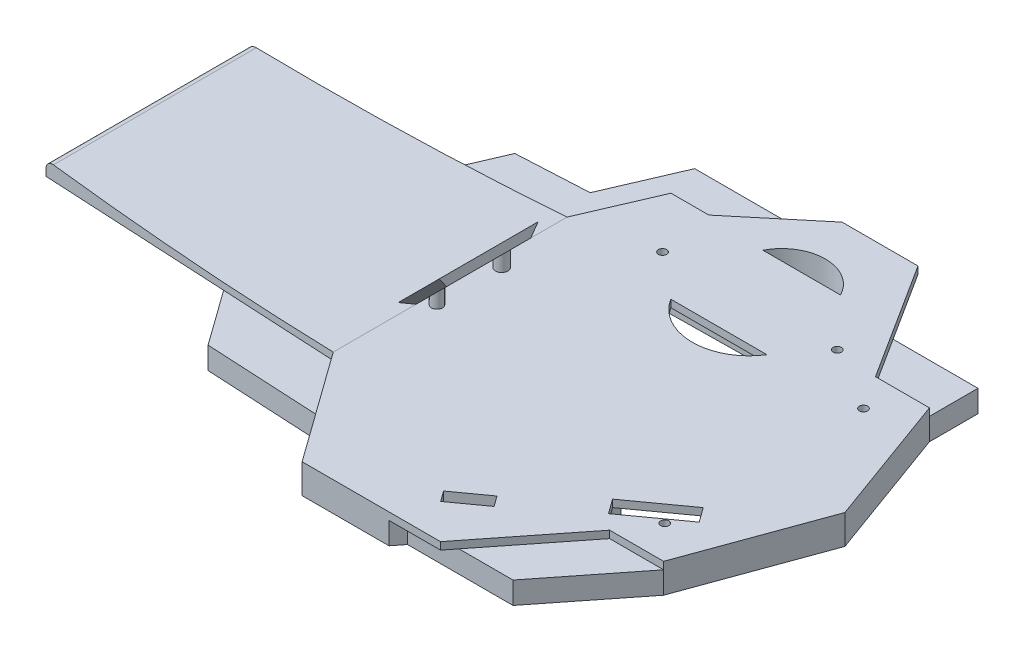
SolidWorks part; units mm, degrees
ref_plane "前视基准面" through (0, 0, 0) normal (0, 0, 1) x (1, 0, 0)
ref_plane "上视基准面" through (0, 0, 0) normal (0, 1, 0) x (1, 0, 0)
ref_plane "右视基准面" through (0, 0, 0) normal (1, 0, 0) x (0, 0, -1)
other "Configuration Table"
sketch "草图2" plane through (0, 0, 0) normal (0, 1, 0) x (1, 0, 0)
  line L0 (0, 0) -> (243.6421, 0) construction
  line L30 (176.8295, 36.1855) -> (82.5273, -31.8251) construction
  line L35 (141.8216, 68.0827) -> (121.1619, 68.0827)
  line L36 (176.8295, 36.1855) -> (190, 0)
  line L37 (104.1466, -61.9173) -> (82.5273, -31.8251)
  line L38 (82.5273, -31.8251) -> (0, -27.5)
  line L39 (0, -27.5) -> (0, 27.5)
  line L40 (0, 27.5) -> (82.5273, 31.8251)
  line L43 (190, 0) -> (176.8295, -36.1855)
  line L45 (82.5273, 31.8251) -> (91.0398, 51.6089)
  line L51 (104.1466, -61.9173) -> (190, 0) construction
  line L53 (141.8216, -61.9173) -> (104.1466, -61.9173)
  line L55 (82.5273, 31.8251) -> (342.4089, 31.8251) construction
  line L57 (176.8295, 36.1855) -> (176.8295, 0) construction
  line L58 (176.8295, 0) -> (176.8295, -36.1855) construction
  line L59 (82.5273, -31.8251) -> (342.4089, -31.8251) construction
  line L62 (91.0398, 51.6089) -> (101.351, 51.6089)
  line L63 (101.351, 51.6089) -> (121.1619, 68.0827)
  line L64 (141.8216, 68.0827) -> (162.1337, 36.1855)
  line L65 (162.1337, 36.1855) -> (176.8295, 36.1855)
  line L66 (176.8295, -36.1855) -> (162.1337, -36.1855)
  line L67 (162.1337, -36.1855) -> (141.8216, -61.9173)
  dimension "D1" = 190
  dimension "D2" = 130
  dimension "D4" = 55
  dimension "D6" = 93
  dimension "D7" = 93
  dimension "D8" = 140
extrude "凸台-拉伸1" add sketch "草图2" along normal blind 2
sketch "草图6" plane through (0, 2, 0) normal (0, 1, 0) x (1, 0, 0)
  line L0 (82.5273, 31.8251) -> (82.5273, -31.8251)
  line L1 (82.5273, -31.8251) -> (0, -27.5)
  line L2 (0, -27.5) -> (0, 27.5)
  line L3 (0, 27.5) -> (82.5273, 31.8251)
extrude "凸台-拉伸2" add sketch "草图6" along normal blind 2
sketch "草图7" plane through (0, 0, 0) normal (0, 0, 1) x (1, 0, 0)
  line L2 (82.5273, 2) -> (82.5273, 30.7408)
  line L3 (82.5273, 30.7408) -> (0, 4)
  spline S0 degree 2 poles (82.5273, 2) (41.2153, 1.0012) (0, 4) knots 0 0 0 1 1 1
extrude "切除-拉伸3" cut sketch "草图7" against normal through all both and the other way through all
fillet "圆角1" radius 2 1 edges at (0, 4, 0)
ref_plane "基准面3" through (0, -12, 0) normal (0, -1, 0) x (-1, 0, 0)
sketch "草图10" plane through (0, 0, 0) normal (0, -1, 0) x (1, 0, 0)
  line L0 (0, 27.5) -> (82.5273, 31.8251)
  line L1 (82.5273, 31.8251) -> (171.8529, 31.8251)
  line L2 (171.8529, 31.8251) -> (171.8529, -31.8251)
  line L3 (171.8529, -31.8251) -> (82.5273, -31.8251)
  line L4 (82.5273, -31.8251) -> (0, -27.5)
  line L5 (0, -27.5) -> (0, 27.5)
sketch "草图12" plane through (0, 2, 0) normal (0, 1, 0) x (1, 0, 0)
  line L0 (176.8295, 36.1855) -> (82.5273, -31.8251)
  line L1 (190, 0) -> (104.1466, -61.9173)
  line L2 (183.4148, 18.0928) -> (93.337, -46.8712) construction
  line L3 (190, 0) -> (176.8295, 36.1855) construction
  line L4 (82.5273, -31.8251) -> (104.1466, -61.9173) construction
sketch "草图13" plane through (0, 0, 0) normal (0, -1, 0) x (1, 0, 0)
  line L0 (53.5015, -30.3039) -> (58.4123, -41.717)
  line L1 (82.5273, -31.8251) -> (0, -27.5) construction
  line L2 (58.4123, -41.717) -> (77.9269, -42.7397)
  line L3 (77.9269, -42.7397) -> (86.4844, -62.6282)
  line L4 (86.4844, -62.6282) -> (136.1647, -62.6282)
  line L5 (176.8295, 36.1855) -> (190, 0)
  line L6 (190, 0) -> (176.8295, -36.1855)
  line L7 (136.1647, -62.6282) -> (144.5841, -49.4069)
  line L8 (144.5841, -49.4069) -> (176.8295, -49.4069)
  line L9 (176.8295, -49.4069) -> (176.8295, -36.1855)
  line L11 (176.8295, 36.1855) -> (158.7432, 59.0976)
  line L12 (158.7432, 59.0976) -> (130.0164, 59.0976)
  line L13 (130.0164, 59.0976) -> (127.7906, 61.9173)
  line L14 (104.1466, 61.9173) -> (141.8216, 61.9173) construction
  line L15 (127.7906, 61.9173) -> (104.1466, 61.9173)
  line L16 (104.1466, 61.9173) -> (93.337, 46.8712)
  line L17 (93.337, 46.8712) -> (61.8459, 45.2208)
  line L18 (61.8459, 45.2208) -> (51.0363, 30.1747)
  line L19 (0, 27.5) -> (82.5273, 31.8251) construction
  line L20 (51.0363, 30.1747) -> (171.8529, 31.8251)
  line L21 (171.8529, 31.8251) -> (171.8529, -31.8251)
  line L22 (171.8529, -31.8251) -> (53.5015, -30.3039)
extrude "凸台-拉伸4" add sketch "草图13" along normal blind 6 contours L18 L20 L21 L22 L0 L2 L3 L4 L7 L8 L9 L6 L5 L11 L12 L13 L15 L16 L17
sketch "草图17" plane through (0, 2, 0) normal (0, 1, 0) x (1, 0, 0)
  line L3 (116.0112, 26.5953) -> (142.1812, 26.5953)
  line L4 (138.1274, 50.6813) -> (116.9896, 50.6813)
  arc A1 (116.0112, 26.5953) -> (142.1812, 26.5953) centre (129.0962, 34.7996) ccw
  arc A2 (116.9896, 50.6813) -> (138.1274, 50.6813) centre (127.5585, 45.2443) cw
sketch "草图18" plane through (0, 2, 0) normal (0, 1, 0) x (1, 0, 0)
  line L4 (169.5639, -18.1259) -> (155.2183, -28.4719)
  line L5 (172.4314, -22.1019) -> (169.5639, -18.1259)
  line L6 (158.0858, -32.4479) -> (172.4314, -22.1019)
  line L7 (155.2183, -28.4719) -> (158.0858, -32.4479)
  line L8 (169.5639, -18.1259) -> (155.2183, -28.4719)
  line L9 (172.4314, -22.1019) -> (169.5639, -18.1259)
  line L10 (158.0858, -32.4479) -> (172.4314, -22.1019)
  line L11 (155.2183, -28.4719) -> (158.0858, -32.4479)
  line L12 (130.3021, -49.5646) -> (132.3616, -52.4203)
  line L13 (132.3616, -52.4203) -> (140.8147, -46.3239)
  line L14 (140.8147, -46.3239) -> (138.7552, -43.4683)
  line L15 (138.7552, -43.4683) -> (130.3021, -49.5646)
  line L16 (130.3021, -49.5646) -> (132.3616, -52.4203)
  line L17 (132.3616, -52.4203) -> (140.8147, -46.3239)
  line L18 (140.8147, -46.3239) -> (138.7552, -43.4683)
  line L19 (138.7552, -43.4683) -> (130.3021, -49.5646)
  dimension "D1" = 0
  dimension "D2" = 0
extrude "切除-拉伸7" cut sketch "草图18" against normal through all
sketch "草图19" plane through (0, 2, 0) normal (0, 1, 0) x (1, 0, 0)
  line L0 (82.5273, -31.8251) -> (176.8295, 36.1855)
  line L1 (176.8295, 36.1855) -> (190, 0)
  line L2 (190, 0) -> (104.1466, -61.9173)
  line L3 (104.1466, -61.9173) -> (82.5273, -31.8251)
ref_plane "基准面4" through (40.2637, -40.2637, 0) normal (-0.7071, 0.7071, 0) x (0, 0, -1)
sketch "草图23" plane through (40.2637, -40.2637, 0) normal (-0.7071, 0.7071, 0) x (0, 0, -1)
  line L0 (-9.292, -59.7699) -> (13.6381, -59.7699)
  line L1 (-31.8251, -59.7699) -> (31.8251, -59.7699) construction
  line L2 (13.6381, -59.7699) -> (13.6381, -71.5206)
  line L3 (13.6381, -71.5206) -> (-9.292, -71.5206)
  line L4 (-9.292, -71.5206) -> (-9.292, -60.8098)
  line L5 (-9.292, -60.8098) -> (-9.292, -59.7699)
  point P7 (0, 0)
extrude "凸台-拉伸5" add sketch "草图23" along normal blind 2 draft 45 separate body draft outward yes
sketch "草图24" plane through (0, 2, 0) normal (0, 1, 0) x (1, 0, 0)
  circle A0 centre (85.4903, 11.0478) radius 1.6973
  circle A1 centre (85.4903, -6.5413) radius 1.5
  point P4 (0, 0)
  point P5 (0, 0)
  point P6 (85.4903, 11.0478)
  point P7 (85.4903, -6.5413)
  point P8 (0, 0)
  point P9 (0, 0)
extrude "凸台-拉伸11" add sketch "草图24" along normal up to surface (2.9629 mm away) separate body contours A0 | A1
ref_plane "基准面6" through (0, 4, 0) normal (0, 1, 0) x (1, 0, 0)
sketch "草图25" plane through (0, 4, 0) normal (0, 1, 0) x (1, 0, 0)
  line L1 (67.0613, -53.2409) -> (67.0613, 49.4655) construction
  line L2 (-9.3986, 0) -> (224.1358, 0) construction
  circle A0 centre (67.0613, -25.5664) radius 3
  circle A1 centre (67.0613, 25.5664) radius 3
  circle A2 centre (168.0155, 27.0476) radius 1
  circle A3 centre (168.0155, -27.0476) radius 1
  circle A4 centre (150.7888, 25.9399) radius 3
  circle A5 centre (150.7888, -25.9399) radius 3
  point P11 (168.0155, 27.0476)
  point P14 (168.0155, -27.0476)
extrude "切除-拉伸8" cut sketch "草图17" against normal through all
hole_wizard "#4-40 螺纹孔3" positions "草图25" profile "草图26" tap size "#4-40" standard "ANSI Inch" end condition through all
sketch "草图26" plane through (168.0155, 4, 27.0476) normal (1, 0, 0) x (0, 0, 1)
  line L0 (0, 0) -> (0, 10)
  line L1 (0, 10) -> (1.1303, 10)
  line L2 (1.1303, 10) -> (1.1303, 0)
  line L5 (1.1303, 0) -> (0, 0)
  line L11 (0, -6.35) -> (0, 107.95) construction
  dimension "通孔螺纹孔钻头直径" = 2.2606
  dimension "通孔螺纹孔钻头深度" = 10
cosmetic thread "孔螺纹线4" parameters "D2"=2.8448
cosmetic thread "孔螺纹线5" parameters "D2"=2.8448
sketch "草图29" plane through (0, 0, 0) normal (0, -1, 0) x (1, 0, 0)
  circle A0 centre (67.0613, 25.5664) radius 3
  circle A1 centre (67.0613, -25.5664) radius 3
  circle A2 centre (150.7888, 25.9399) radius 3
  circle A3 centre (150.7888, -25.9399) radius 3
extrude "凸台-拉伸14" add sketch "草图29" along normal blind 5 contours A0 | A1 | A2 | A3
sketch "草图33" plane through (0, 2, 0) normal (0, 1, 0) x (1, 0, 0)
  point P0 (150.5968, 37.3353)
  point P3 (103.7494, 36.6082)
hole_wizard "#4-40 螺纹孔4" positions "草图33" profile "草图32" tap size "#4-40" standard "ANSI Inch" end condition through all
sketch "草图32" plane through (150.5968, 2, -37.3353) normal (1, 0, 0) x (0, 0, 1)
  line L0 (0, 0) -> (0, 8)
  line L1 (0, 8) -> (1.1303, 8)
  line L2 (1.1303, 8) -> (1.1303, 0)
  line L5 (1.1303, 0) -> (0, 0)
  line L11 (0, -6.35) -> (0, 107.95) construction
  dimension "通孔螺纹孔钻头直径" = 2.2606
  dimension "通孔螺纹孔钻头深度" = 8
cosmetic thread "孔螺纹线8" parameters "D2"=2.8448
cosmetic thread "孔螺纹线9" parameters "D2"=2.8448
